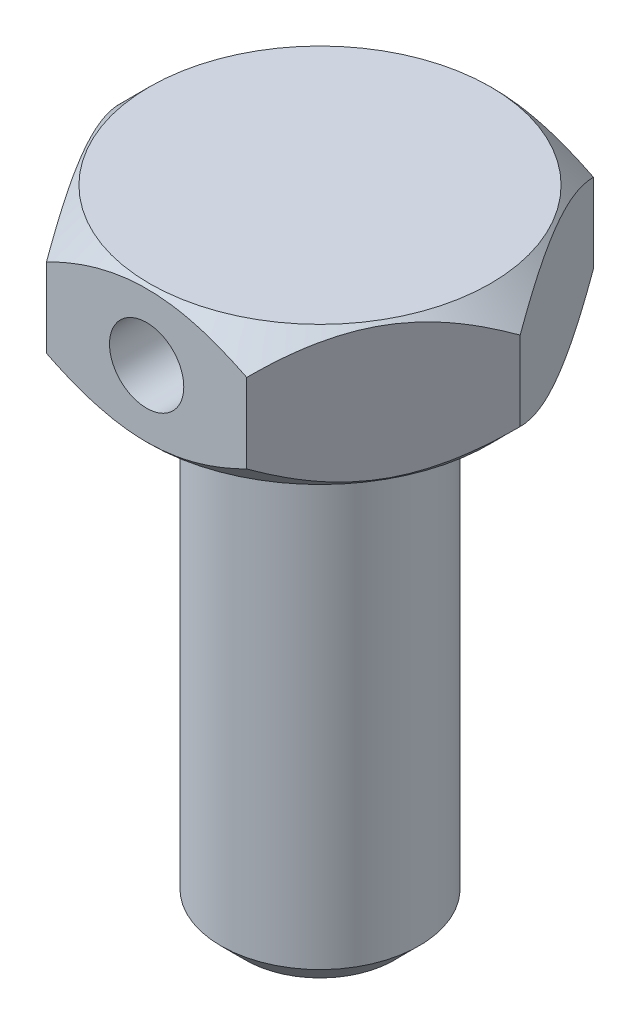
SolidWorks part; units mm, degrees
ref_plane "Спереди" through (0, 0, 0) normal (0, 0, 1) x (1, 0, 0)
ref_plane "Сверху" through (0, 0, 0) normal (0, 1, 0) x (1, 0, 0)
ref_plane "Справа" through (0, 0, 0) normal (1, 0, 0) x (0, 0, -1)
sketch "Эскиз1" plane through (0, 0, 0) normal (0, 1, 0) x (1, 0, 0)
  line L0 (-2.0207, 3.5) -> (2.0207, 3.5)
  line L1 (2.0207, 3.5) -> (4.0415, 0)
  line L2 (4.0415, 0) -> (2.0207, -3.5)
  line L3 (2.0207, -3.5) -> (-2.0207, -3.5)
  line L4 (-2.0207, -3.5) -> (-4.0415, 0)
  line L5 (-4.0415, 0) -> (-2.0207, 3.5)
  dimension "D5" = 3.5
  dimension "D2" = 120
  dimension "D3" = 120
  dimension "D4" = 120
  dimension "D6" = 3.5
  dimension "D7" = 3.5
  dimension "D8" = 3.5
  dimension "D9" = 3.5
  dimension "D10" = 120
  dimension "D11" = 3.5
extrude "Вытянуть1" add sketch "Эскиз1" against normal blind 2.8
sketch "Эскиз5" plane through (0, -2.8, 0) normal (0, -1, 0) x (1, 0, 0)
  circle A0 centre (0, 0) radius 2
  dimension "D1" = 4
extrude "Вытянуть2" add sketch "Эскиз5" along normal blind 10
chamfer "Фаска1" distance 0.5 angle 45 1 edges at (0, -12.8, -2)
ref_axis "Ось1" through (0, -2.8, 0) along (0, -1, 0)
ref_plane "Плоскость1" through (0, 0, 0) normal (0, 0, 1) x (1, 0, 0)
sketch "Эскиз4" plane through (0, 0, 0) normal (0, 0, 1) x (1, 0, 0)
  line L0 (-4.0415, -0.6) -> (-3.4415, 0)
  line L1 (-4.0415, -2.8) -> (-4.0415, 0) construction
  line L2 (-4.0415, 0) -> (-2.0207, 0) construction
  line L3 (-3.4415, 0) -> (-4.0415, 0)
  line L4 (-4.0415, 0) -> (-4.0415, -0.6)
  line L5 (-4.0415, -2.2) -> (-3.4415, -2.8)
  line L6 (-4.0415, -2.8) -> (-2.0207, -2.8) construction
  line L7 (-3.4415, -2.8) -> (-4.0415, -2.8)
  line L8 (-4.0415, -2.8) -> (-4.0415, -2.2)
  dimension "D1" = 0.6
  dimension "D2" = 0.6
  dimension "D3" = 0.6
  dimension "D4" = 0.6
revolve "Вырез-Повернуть1" cut sketch "Эскиз4" angle 360 about axis through (0, -2.8, 0) along (0, -1, 0)
sketch "Эскиз6" plane through (0, 0, 3.5) normal (0, 0, 1) x (1, 0, 0)
  line L0 (0, -1.4) -> (0, 0) construction
  line L2 (3.4415, 0) -> (-3.4415, 0) construction
  circle A0 centre (0, -1.4) radius 0.75
  dimension "D1" = 1.5
  dimension "D2" = 1.4
extrude "Вырез-Вытянуть1" cut sketch "Эскиз6" against normal through all
